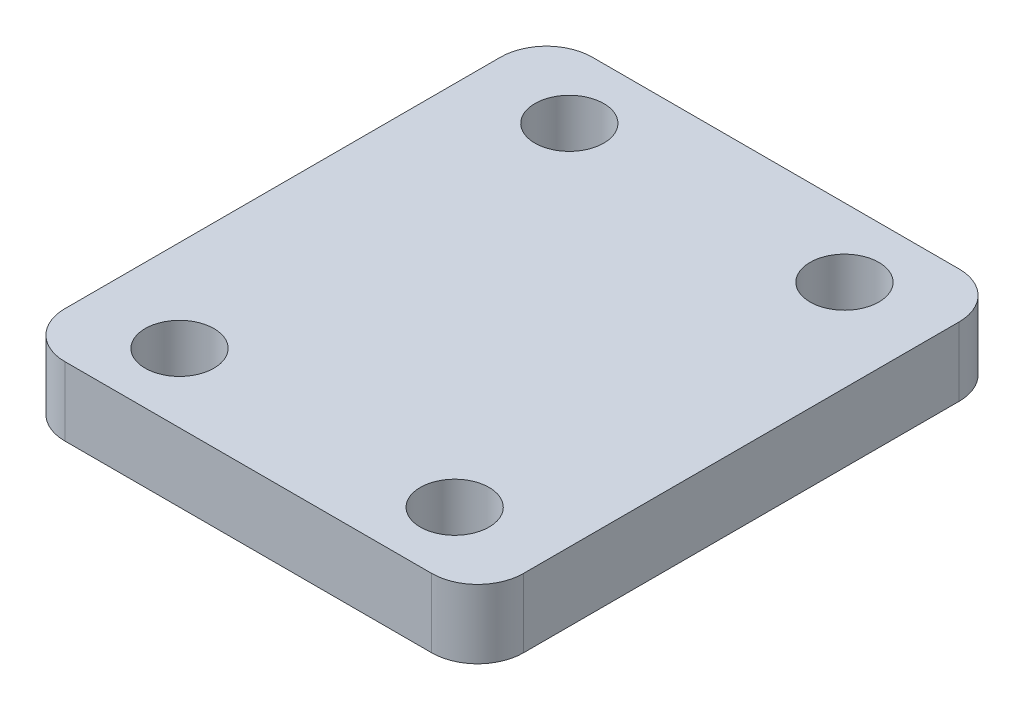
SolidWorks part; units mm, degrees
material "聚脂树脂"
ref_plane "前视基准面" through (0, 0, 0) normal (0, 0, 1) x (1, 0, 0)
ref_plane "上视基准面" through (0, 0, 0) normal (0, 1, 0) x (1, 0, 0)
ref_plane "右视基准面" through (0, 0, 0) normal (1, 0, 0) x (0, 0, -1)
other "Configuration Table"
sketch "草图1" plane through (0, 0, 0) normal (0, 1, 0) x (1, 0, 0)
  line L0 (0, 0) -> (0, 19.7204) construction
  line L1 (-10, -11.5) -> (10, -11.5)
  line L2 (-10, -11.5) -> (-10, 11.5)
  line L3 (-10, 11.5) -> (10, 11.5)
  line L4 (10, -11.5) -> (10, 11.5)
  line L5 (-10, -11.5) -> (10, 11.5) construction
  line L6 (-10, 11.5) -> (10, -11.5) construction
  line L7 (0, 0) -> (18.5801, 0) construction
  circle A0 centre (-6, 8.5) radius 1.5
  circle A1 centre (6, 8.5) radius 1.5
  circle A2 centre (6, -8.5) radius 1.5
  circle A3 centre (-6, -8.5) radius 1.5
  point P0 (0, 0)
  dimension "D3" = 3
  dimension "D4" = 12
  dimension "D5" = 17
  dimension "D1" = 20
  dimension "D2" = 23
extrude "凸台-拉伸1" add sketch "草图1" along normal blind 3
fillet "圆角1" radius 2 4 edges at (10, 1.5, 11.5) (-10, 1.5, 11.5) (10, 1.5, -11.5) (-10, 1.5, -11.5)
